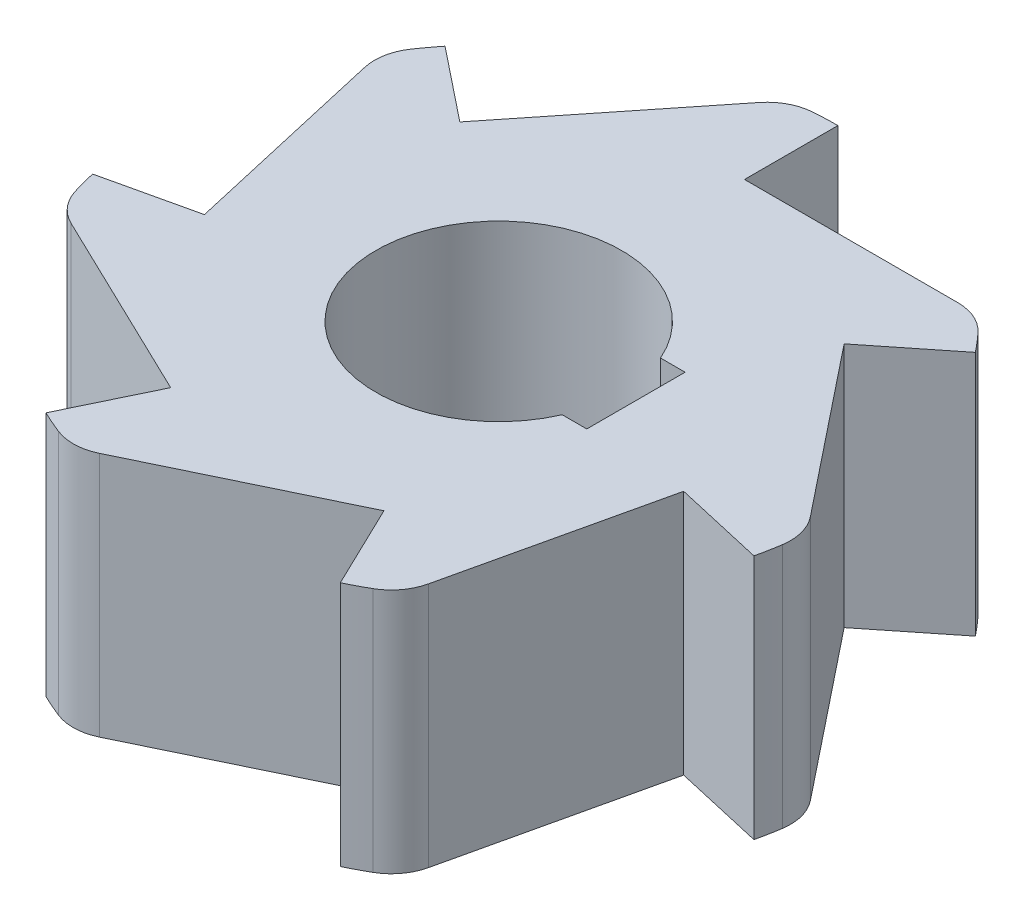
SolidWorks part; units mm, degrees
ref_plane "Front Plane" through (0, 0, 0) normal (0, 0, 1) x (1, 0, 0)
ref_plane "Top Plane" through (0, 0, 0) normal (0, 1, 0) x (1, 0, 0)
ref_plane "Right Plane" through (0, 0, 0) normal (1, 0, 0) x (0, 0, -1)
sketch "Sketch1" plane through (0, 0, 0) normal (0, 1, 0) x (1, 0, 0)
  line L0 (0, 0) -> (0, 50) construction
  line L2 (0, 50) -> (43.3705, 50)
  line L3 (0, 50) -> (43.3705, 50)
  line L4 (0, 0) -> (53.9464, 43.0208) construction
  line L5 (53.9464, 43.0208) -> (39.0916, 31.1745)
  line L6 (67.27, -15.3539) -> (48.7464, -11.126)
  line L7 (39.0916, 31.1745) -> (66.1326, -2.7339)
  line L8 (29.938, -62.1669) -> (21.6942, -45.0484)
  line L9 (48.7464, -11.126) -> (39.0956, -53.4092)
  line L10 (-29.938, -62.1669) -> (-21.6942, -45.0484)
  line L11 (21.6942, -45.0484) -> (-17.3813, -63.8662)
  line L12 (-67.27, -15.3539) -> (-48.7464, -11.126)
  line L13 (-21.6942, -45.0484) -> (-60.7697, -26.2307)
  line L14 (-53.9464, 43.0208) -> (-39.0916, 31.1745)
  line L15 (-48.7464, -11.126) -> (-58.3972, 31.1571)
  line L16 (0, 69) -> (0, 50)
  line L17 (-39.0916, 31.1745) -> (-12.0505, 65.0829)
  line L21 (27.9129, -10) -> (27.9129, 10)
  line L22 (27.9129, -10) -> (22.9129, -10)
  line L23 (27.9129, 10) -> (22.9129, 10)
  arc A0 (22.9129, 10) -> (22.9129, -10) centre (0, 0) ccw
  circle A1 centre (0, 0) radius 50
  arc A4 (50.7214, 46.7797) -> (53.9464, 43.0208) centre (0, 0) cw
  arc A5 (22.9129, 10) -> (22.9129, -10) centre (0, 0) ccw
  circle A6 centre (0, 0) radius 69 construction
  arc A7 (22.9129, 10) -> (22.9129, -10) centre (0, 0) ccw
  arc A8 (68.1981, -10.489) -> (66.1326, -2.7339) centre (58.3143, -8.9688) ccw
  arc A9 (22.9129, 10) -> (22.9129, -10) centre (0, 0) ccw
  arc A11 (22.9129, 10) -> (22.9129, -10) centre (0, 0) ccw
  arc A13 (22.9129, 10) -> (22.9129, -10) centre (0, 0) ccw
  arc A15 (22.9129, 10) -> (22.9129, -10) centre (0, 0) ccw
  arc A17 (22.9129, 10) -> (22.9129, -10) centre (0, 0) ccw
  arc A18 (68.1981, -10.489) -> (67.27, -15.3539) centre (0, 0) cw
  arc A21 (34.3202, -59.8592) -> (39.0956, -53.4092) centre (29.3463, -51.1839) ccw
  arc A22 (34.3202, -59.8592) -> (29.938, -62.1669) centre (0, 0) cw
  arc A23 (-25.4015, -64.1542) -> (-17.3813, -63.8662) centre (-21.7201, -54.8565) ccw
  arc A24 (50.7214, 46.7797) -> (43.3705, 50) centre (43.3705, 40) ccw
  arc A25 (53.9464, 43.0208) -> (50.7214, 46.7797) centre (0, 0) ccw construction
  arc A26 (-25.4015, -64.1542) -> (-29.938, -62.1669) centre (0, 0) cw
  circle A27 centre (0, 0) radius 70 construction
  arc A28 (-65.9954, -20.1398) -> (-60.7697, -26.2307) centre (-56.4308, -17.221) ccw
  arc A29 (-65.9954, -20.1398) -> (-67.27, -15.3539) centre (0, 0) cw
  arc A30 (-56.8934, 39.0403) -> (-58.3972, 31.1571) centre (-48.648, 33.3823) ccw
  arc A31 (-56.8934, 39.0403) -> (-53.9464, 43.0208) centre (0, 0) cw
  arc A32 (-4.9495, 68.8223) -> (-12.0505, 65.0829) centre (-4.2322, 58.848) ccw
  arc A33 (-4.9495, 68.8223) -> (0, 69) centre (0, 0) cw
  point P16 (25, 0)
  point P42 (0, 0)
  point P55 (0, 0)
  point P60 (0, 0)
  point P71 (0, 0)
  point P72 (0, 0)
  point P80 (0, 0)
  dimension "D1" = 50
  dimension "D2" = 100
  dimension "D3" = 138
  dimension "D5" = 20
  dimension "D10" = 140
  dimension "D6" = 10
  dimension "D7" = 7
  dimension "D8" = 5
  dimension "D4" = 8
extrude "Boss-Extrude1" add sketch "Sketch1" along normal blind 50
